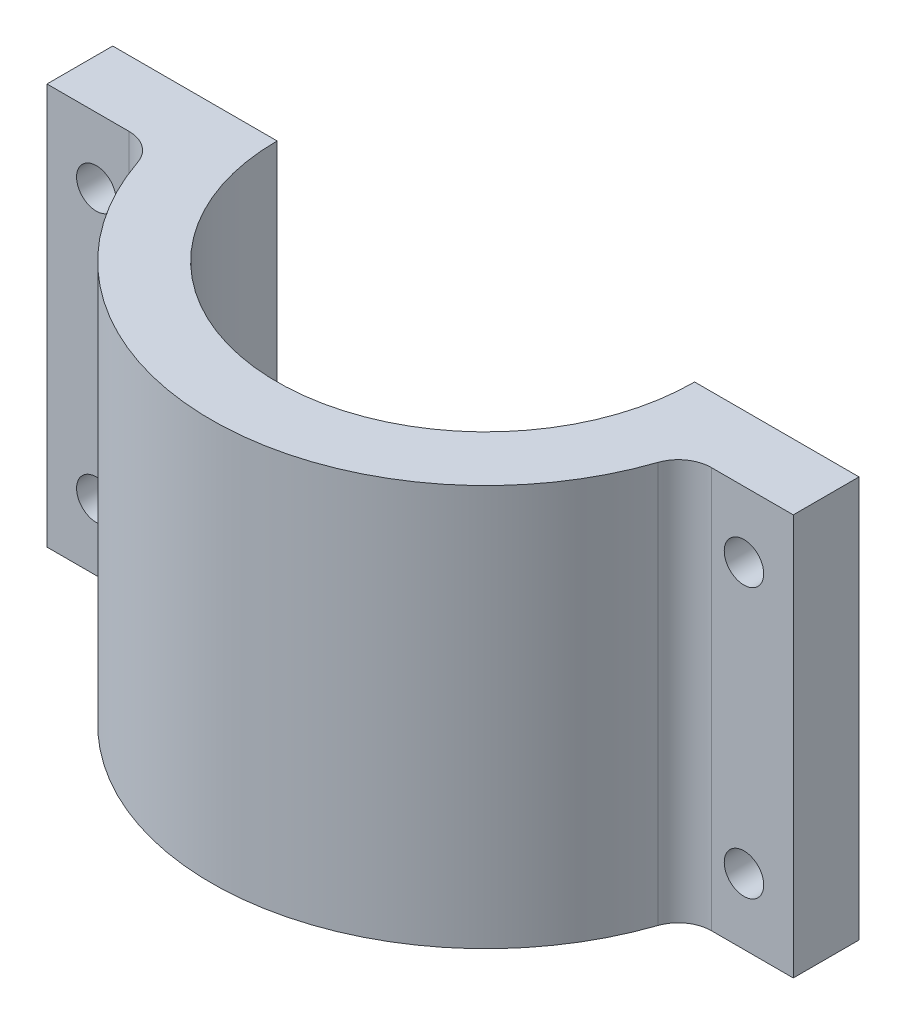
SolidWorks part; units mm, degrees
ref_plane "Front Plane" through (0, 0, 0) normal (0, 0, 1) x (1, 0, 0)
ref_plane "Top Plane" through (0, 0, 0) normal (0, 1, 0) x (1, 0, 0)
ref_plane "Right Plane" through (0, 0, 0) normal (1, 0, 0) x (0, 0, -1)
sketch "Sketch1" plane through (0, 0, 0) normal (0, 1, 0) x (1, 0, 0)
  line L0 (-31.75, 0) -> (-41.75, 0)
  line L1 (31.75, 0) -> (41.75, 0)
  line L2 (-41.75, 0) -> (-56.75, 0)
  line L3 (-56.75, 0) -> (-56.75, -10)
  line L4 (-56.75, -10) -> (-40.5347, -10)
  line L5 (41.75, 0) -> (56.75, 0)
  line L6 (56.75, 0) -> (56.75, -10)
  line L7 (56.75, -10) -> (40.5347, -10)
  arc A0 (-31.75, 0) -> (31.75, 0) centre (0, 0) ccw
  arc A1 (-40.5347, -10) -> (40.5347, -10) centre (0, 0) ccw
  circle A2 centre (0, 0) radius 41.75 construction
  circle A3 centre (0, 0) radius 31.75 construction
  dimension "D1" = 63.5
  dimension "D3" = 10
  dimension "D4" = 15
  dimension "D5" = 15
  dimension "D6" = 10
  dimension "D2" = 10
extrude "Boss-Extrude1" add sketch "Sketch1" along normal blind 61
sketch "Sketch2" plane through (0, 0, 10) normal (0, 0, 1) x (1, 0, 0)
  line L0 (0, 61) -> (0, 0) construction
  line L1 (40.5347, 61) -> (-40.5347, 61) construction
  line L2 (-56.75, 61) -> (-40.5347, 61) construction
  line L3 (-56.75, 0) -> (-40.5347, 0) construction
  line L4 (-56.75, 61) -> (-56.75, 0) construction
  circle A0 centre (-49.25, 51) radius 3
  circle A1 centre (-49.25, 10) radius 3
  circle A2 centre (49.25, 10) radius 3
  circle A3 centre (49.25, 51) radius 3
  point P15 (0, 0)
  dimension "D1" = 6
  dimension "D2" = 10
  dimension "D3" = 10
  dimension "D4" = 7.5
extrude "Cut-Extrude1" cut sketch "Sketch2" against normal through all
fillet "Fillet1" radius 5 2 edges at (40.5347, 30.5, 10) (-40.5347, 30.5, 10)
